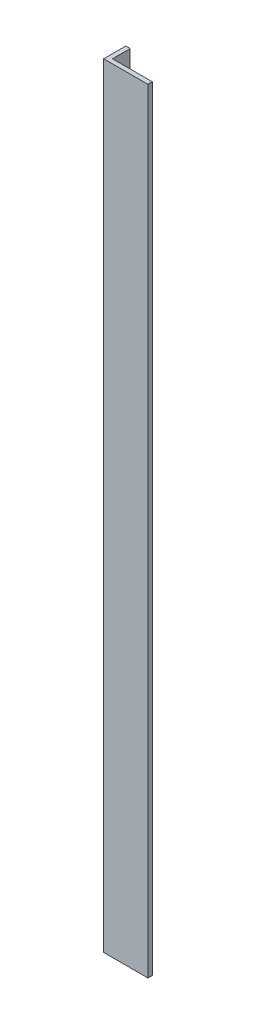
SolidWorks part; units mm, degrees
ref_plane "Front Plane" through (0, 0, 0) normal (0, 0, 1) x (1, 0, 0)
ref_plane "Top Plane" through (0, 0, 0) normal (0, 1, 0) x (1, 0, 0)
ref_plane "Right Plane" through (0, 0, 0) normal (1, 0, 0) x (0, 0, -1)
sketch "Sketch1" plane through (0, 0, 0) normal (0, 1, 0) x (1, 0, 0)
  line L0 (0, 0) -> (0, 10)
  line L1 (0, 10) -> (2, 10)
  line L2 (2, 10) -> (2, 2)
  line L3 (2, 2) -> (20, 2)
  line L4 (20, 2) -> (20, 0)
  line L5 (20, 0) -> (0, 0)
extrude "Boss-Extrude1" add sketch "Sketch1" along normal up to surface (350 mm away)
